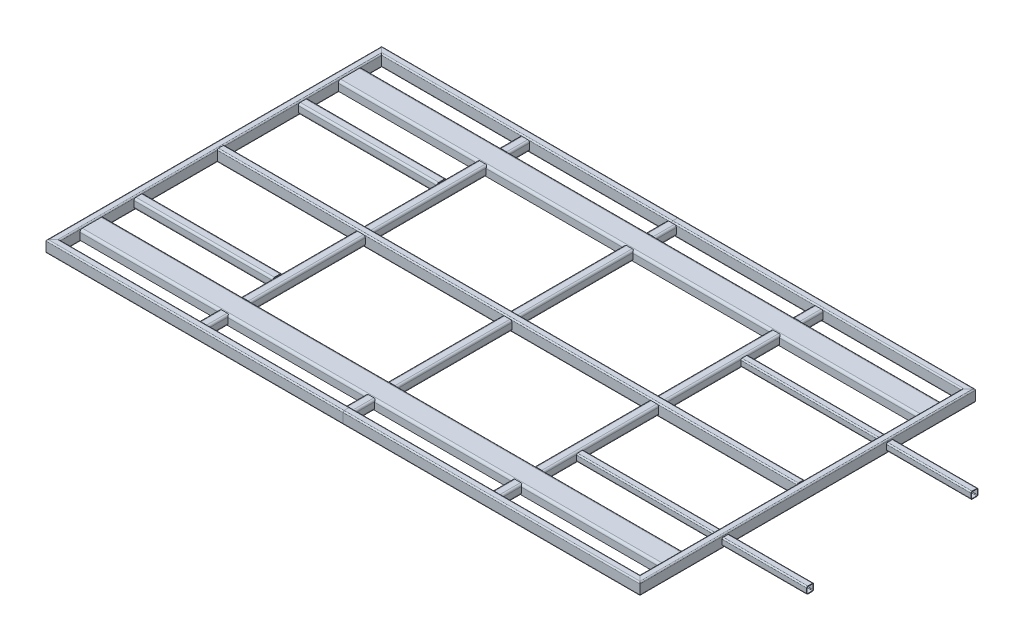
SolidWorks part; units mm, degrees
ref_plane "Front Plane" through (0, 0, 0) normal (0, 0, 1) x (1, 0, 0)
ref_plane "Top Plane" through (0, 0, 0) normal (0, 1, 0) x (1, 0, 0)
ref_plane "Right Plane" through (0, 0, 0) normal (1, 0, 0) x (0, 0, -1)
sketch3d "3DSketch2"
  line L0 (-1250, 0, 200) -> (1250, 0, 200) construction
  line L2 (-1250, 0, 0) -> (-1250, 0, 1400)
  line L5 (-1250, 0, 1200) -> (1250, 0, 1200) construction
  line L7 (0, 0, 0) -> (1250, 0, 0)
  line L13 (1250, 0, 0) -> (1250, 0, 1400)
  line L14 (0, 0, 1400) -> (1250, 0, 1400)
  line L15 (1250, 0, 700) -> (-1250, 0, 700)
  line L17 (-1250, 0, 0) -> (0, 0, 0)
  line L19 (-1250, 0, 1400) -> (0, 0, 1400)
  dimension "D3" = 200
  dimension "D10" = 1250
  dimension "D2" = 200
  dimension "D4" = 1400
  dimension "D5" = 2500
other "Rectangular tube - configured 50 X 30 X 2.6(1)"
ref_plane "Plane2" through (-1250, 0, 0) normal (0, 0, 1) x (1, 0, 0)
sketch "Sketch1" plane through (-1250, 0, 0) normal (0, 0, 1) x (1, 0, 0)
  line L0 (-9.8, -22.4) -> (9.8, -22.4)
  line L1 (-12.4, -19.8) -> (-12.4, 19.8)
  line L2 (9.8, 22.4) -> (-9.8, 22.4)
  line L3 (12.4, 19.8) -> (12.4, -19.8)
  line L4 (-9.8, -25) -> (9.8, -25)
  line L5 (-15, -19.8) -> (-15, 19.8)
  line L6 (9.8, 25) -> (-9.8, 25)
  line L7 (15, 19.8) -> (15, -19.8)
  arc A0 (15, 19.8) -> (9.8, 25) centre (9.8, 19.8) ccw
  arc A1 (9.8, -25) -> (15, -19.8) centre (9.8, -19.8) ccw
  arc A2 (-15, -19.8) -> (-9.8, -25) centre (-9.8, -19.8) ccw
  arc A3 (-9.8, 25) -> (-15, 19.8) centre (-9.8, 19.8) ccw
  arc A4 (-9.8, 22.4) -> (-12.4, 19.8) centre (-9.8, 19.8) ccw
  arc A5 (12.4, 19.8) -> (9.8, 22.4) centre (9.8, 19.8) ccw
  arc A6 (9.8, -22.4) -> (12.4, -19.8) centre (9.8, -19.8) ccw
  arc A7 (-12.4, -19.8) -> (-9.8, -22.4) centre (-9.8, -19.8) ccw
  point P0 (0, 25)
  point P1 (15, 0)
  point P2 (0, -25)
  point P3 (-15, 0)
  point P4 (-15, 25)
  point P5 (15, 25)
  point P6 (15, -25)
  point P7 (-15, -25)
  point P8 (0, 0)
  point P33 (0, 0)
  dimension "D1" = 5.2
  dimension "Thickness" = 2.6
  dimension "V_leg" = 50
  dimension "H_leg" = 30
sketch "Sketch113" plane through (-1235, 0, 0) normal (1, 0, 0) x (0, 0, -1)
  line L0 (-1385, 19.8) -> (-15, 19.8) construction
  line L1 (-200, 19.8) -> (-100, 19.8)
  line L2 (-200, 19.8) -> (-200, -19.8)
  line L3 (-200, -19.8) -> (-165, -19.8)
  line L4 (-100, 19.8) -> (-100, -19.8)
  line L5 (-165, -11.8) -> (-165, -19.8)
  line L6 (-192, 11.8) -> (-108, 11.8)
  line L7 (-192, 11.8) -> (-192, -11.8)
  line L8 (-192, -11.8) -> (-165, -11.8)
  line L9 (-108, 11.8) -> (-108, -11.8)
  line L10 (-135, -11.8) -> (-135, -19.8)
  line L11 (-135, -11.8) -> (-108, -11.8)
  line L12 (-135, -19.8) -> (-100, -19.8)
  line L13 (-1385, -19.8) -> (-15, -19.8) construction
  dimension "D1" = 100
  dimension "D2" = 8
  dimension "D4" = 8
  dimension "D5" = 8
  dimension "D3" = 8
  dimension "D6" = 35
extrude "Boss-Extrude1" add sketch "Sketch113" along normal up to surface (2470 mm away) separate body up to face at (1235, 0, 700)
sketch "Sketch115" plane through (-1235, 0, 0) normal (1, 0, 0) x (0, 0, -1)
  line L1 (-165, -28.2) -> (-135, -28.2)
  line L12 (-100, 19.8) -> (-200, 19.8)
  line L13 (-100, -19.8) -> (-100, 19.8)
  line L14 (-135, -19.8) -> (-100, -19.8)
  line L15 (-135, -11.8) -> (-135, -19.8)
  line L16 (-108, -11.8) -> (-135, -11.8)
  line L17 (-108, 11.8) -> (-108, -11.8)
  line L18 (-192, 11.8) -> (-108, 11.8)
  line L19 (-192, -11.8) -> (-192, 11.8)
  line L20 (-165, -11.8) -> (-192, -11.8)
  line L21 (-165, -19.8) -> (-165, -11.8)
  line L22 (-200, -19.8) -> (-165, -19.8)
  line L23 (-200, 19.8) -> (-200, -19.8)
  line L27 (-135, -11.8) -> (-135, -28.2)
  line L28 (-108, -11.8) -> (-135, -11.8)
  line L29 (-108, 11.8) -> (-108, -11.8)
  line L30 (-192, 11.8) -> (-108, 11.8)
  line L31 (-192, -11.8) -> (-192, 11.8)
  line L32 (-165, -11.8) -> (-192, -11.8)
  line L33 (-165, -28.2) -> (-165, -11.8)
  dimension "D2" = 40
  dimension "D1" = 0
fillet "Fillet1" radius 10 2 edges at (0, 19.8, 200) (0, 19.8, 100)
extrude "Cut-Extrude1" cut sketch "Sketch115" against normal blind 30 and the other way blind 30
ref_plane "Plane3" through (0, 0, 700) normal (0, 0, 1) x (1, 0, 0)
mirror "Mirror1" about plane through (0, 0, 700) normal (0, 0, 1) of "Cut-Extrude1", "Fillet1", "Boss-Extrude1"
sketch "Sketch116" plane through (0, 0, 0) normal (0, 1, 0) x (1, 0, 0)
  line L0 (-1235, -105) -> (1235, -105) construction
  line L1 (-1235, -100) -> (-1235, -110) construction
  line L2 (-1235, -195) -> (1235, -195) construction
  line L3 (-1235, -190) -> (-1235, -200) construction
  line L5 (1235, -200) -> (1235, -190) construction
  line L6 (1235, -110) -> (1235, -100) construction
  line L7 (-1235, -1205) -> (1235, -1205) construction
  line L8 (1235, -1210) -> (1235, -1200) construction
  line L9 (-1235, -1210) -> (-1235, -1200) construction
  line L10 (-1235, -1295) -> (1235, -1295) construction
  line L11 (-1235, -1300) -> (-1235, -1290) construction
  line L12 (1235, -1300) -> (1235, -1290) construction
  line L13 (-625, 0) -> (-625, -105)
  line L14 (-1250, 0) -> (0, 0) construction
  line L16 (-625, -195) -> (-625, -1205)
  line L17 (-625, -1295) -> (-625, -1400)
  line L18 (-1250, -1400) -> (0, -1400) construction
  line L19 (0, 9.8) -> (0, -105)
  line L20 (0, -195) -> (0, -1205)
  line L21 (0, -1295) -> (0, -1400)
  line L22 (625, 0) -> (625, -105)
  line L23 (0, 0) -> (1250, 0) construction
  line L24 (625, -195) -> (625, -1205)
  line L25 (625, -1295) -> (625, -1400)
  line L26 (0, -1400) -> (1250, -1400) construction
  line L27 (-1250, -350) -> (-625, -350)
  line L28 (-1250, 0) -> (-1250, -1400) construction
  line L29 (-1250, -1050) -> (-625, -1050)
  line L30 (625, -350) -> (1625, -350)
  line L31 (625, -1050) -> (1625, -1050)
  dimension "D1" = 150
  dimension "D2" = 150
  dimension "D3" = 1000
other "Square tube - configured 40 X 40 X 4(1)"
ref_plane "Plane4" through (-625, 0, 0) normal (0, 0, 1) x (1, 0, 0)
sketch "Sketch119" plane through (-625, 0, 0) normal (0, 0, 1) x (1, 0, 0)
  line L0 (-12, -16) -> (12, -16)
  line L1 (-16, -12) -> (-16, 12)
  line L2 (12, 16) -> (-12, 16)
  line L3 (16, 12) -> (16, -12)
  line L4 (-12, -20) -> (12, -20)
  line L5 (-20, -12) -> (-20, 12)
  line L6 (12, 20) -> (-12, 20)
  line L7 (20, 12) -> (20, -12)
  arc A0 (20, 12) -> (12, 20) centre (12, 12) ccw
  arc A1 (12, -20) -> (20, -12) centre (12, -12) ccw
  arc A2 (-20, -12) -> (-12, -20) centre (-12, -12) ccw
  arc A3 (-12, 20) -> (-20, 12) centre (-12, 12) ccw
  arc A4 (-12, 16) -> (-16, 12) centre (-12, 12) ccw
  arc A5 (16, 12) -> (12, 16) centre (12, 12) ccw
  arc A6 (12, -16) -> (16, -12) centre (12, -12) ccw
  arc A7 (-16, -12) -> (-12, -16) centre (-12, -12) ccw
  point P0 (-20, 0)
  point P1 (20, 0)
  point P2 (0, 20)
  point P3 (0, -20)
  point P4 (0, 0)
  point P5 (-20, -20)
  point P6 (20, -20)
  point P7 (20, 20)
  point P8 (-20, 20)
  point P33 (0, 0)
  dimension "D1" = 8
  dimension "Thickness" = 4
  dimension "V_leg" = 40
other "Square tube - configured 30 X 30 X 2.6(1)"
ref_plane "Plane5" through (625, 0, 350) normal (1, 0, 0) x (0, 0, -1)
sketch "Sketch120" plane through (625, 0, 350) normal (1, 0, 0) x (0, 0, -1)
  line L0 (-9.8, -12.4) -> (9.8, -12.4)
  line L1 (-12.4, -9.8) -> (-12.4, 9.8)
  line L2 (9.8, 12.4) -> (-9.8, 12.4)
  line L3 (12.4, 9.8) -> (12.4, -9.8)
  line L4 (-9.8, -15) -> (9.8, -15)
  line L5 (-15, -9.8) -> (-15, 9.8)
  line L6 (9.8, 15) -> (-9.8, 15)
  line L7 (15, 9.8) -> (15, -9.8)
  arc A0 (15, 9.8) -> (9.8, 15) centre (9.8, 9.8) ccw
  arc A1 (9.8, -15) -> (15, -9.8) centre (9.8, -9.8) ccw
  arc A2 (-15, -9.8) -> (-9.8, -15) centre (-9.8, -9.8) ccw
  arc A3 (-9.8, 15) -> (-15, 9.8) centre (-9.8, 9.8) ccw
  arc A4 (-9.8, 12.4) -> (-12.4, 9.8) centre (-9.8, 9.8) ccw
  arc A5 (12.4, 9.8) -> (9.8, 12.4) centre (9.8, 9.8) ccw
  arc A6 (9.8, -12.4) -> (12.4, -9.8) centre (9.8, -9.8) ccw
  arc A7 (-12.4, -9.8) -> (-9.8, -12.4) centre (-9.8, -9.8) ccw
  point P0 (-15, 0)
  point P1 (15, 0)
  point P2 (0, 15)
  point P3 (0, -15)
  point P4 (0, 0)
  point P5 (-15, -15)
  point P6 (15, -15)
  point P7 (15, 15)
  point P8 (-15, 15)
  point P33 (0, 0)
  dimension "D1" = 5.2
  dimension "Thickness" = 2.6
  dimension "V_leg" = 30
equation "\"D4@Sketch113\"=\"D2@Sketch113\""
equation "\"D5@Sketch113\"=\"D2@Sketch113\""
equation "\"D3@Sketch113\"=\"D2@Sketch113\""
equation "\"D3@3DSketch2\"=\"D2@3DSketch2\""
equation "\"D2@Sketch116\"=\"D1@Sketch116\""
